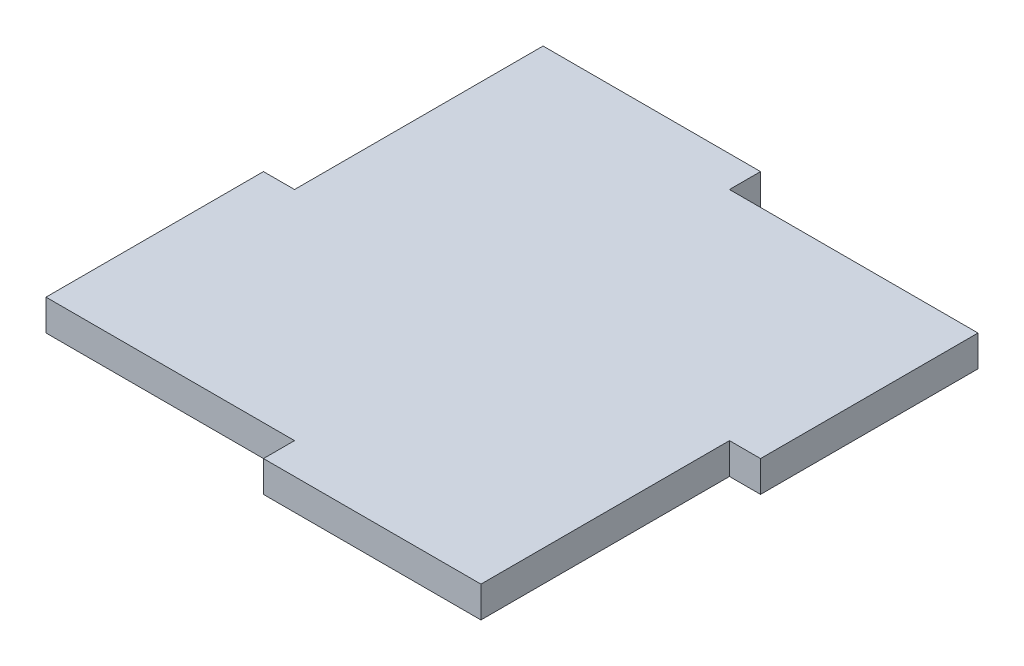
SolidWorks part; units mm, degrees
material "Acrylic (Medium-high impact)"
ref_plane "Front Plane" through (0, 0, 0) normal (0, 0, 1) x (1, 0, 0)
ref_plane "Top Plane" through (0, 0, 0) normal (0, 1, 0) x (1, 0, 0)
ref_plane "Right Plane" through (0, 0, 0) normal (1, 0, 0) x (0, 0, -1)
sketch "Sketch1" plane through (0, 0, 0) normal (0, 1, 0) x (1, 0, 0)
  line L0 (-112.5062, 93.3127) -> (-112.5062, 106.0127)
  line L1 (-112.5062, 93.3127) -> (65.2938, 93.3127)
  line L2 (-112.5062, 93.3127) -> (-112.5062, -84.4873)
  line L3 (-112.5062, -84.4873) -> (65.2938, -84.4873)
  line L4 (65.2938, 93.3127) -> (65.2938, -84.4873)
  line L5 (-112.5062, 106.0127) -> (-23.6062, 106.0127)
  line L6 (-23.6062, 106.0127) -> (-23.6062, 93.3127)
  line L7 (-112.5062, -84.4873) -> (-125.2062, -84.4873)
  line L8 (-125.2062, -84.4873) -> (-125.2062, 4.4127)
  line L9 (-125.2062, 4.4127) -> (-112.5062, 4.4127)
  line L10 (65.2938, -84.4873) -> (65.2938, -97.1873)
  line L11 (65.2938, -97.1873) -> (-23.6062, -97.1873)
  line L12 (-23.6062, -97.1873) -> (-23.6062, -84.4873)
  line L13 (65.2938, 93.3127) -> (77.9938, 93.3127)
  line L14 (77.9938, 93.3127) -> (77.9938, 4.4127)
  line L15 (77.9938, 4.4127) -> (65.2938, 4.4127)
  point P4 (-23.6062, 93.3127)
  point P5 (-112.5062, 4.4127)
  point P9 (65.2938, 4.4127)
  point P10 (-23.6062, -84.4873)
  dimension "D1" = 177.8
  dimension "D2" = 177.8
  dimension "D3" = 12.7
  dimension "D4" = 12.7
  dimension "D5" = 12.7
  dimension "D6" = 12.7
extrude "Boss-Extrude1" add sketch "Sketch1" along normal blind 12.7 contours L9 L8 L7 L2 | L6 L5 L0 L1 | L4 L1 L2 L3 | L15 L14 L13 L4 | L12 L11 L10 L3
